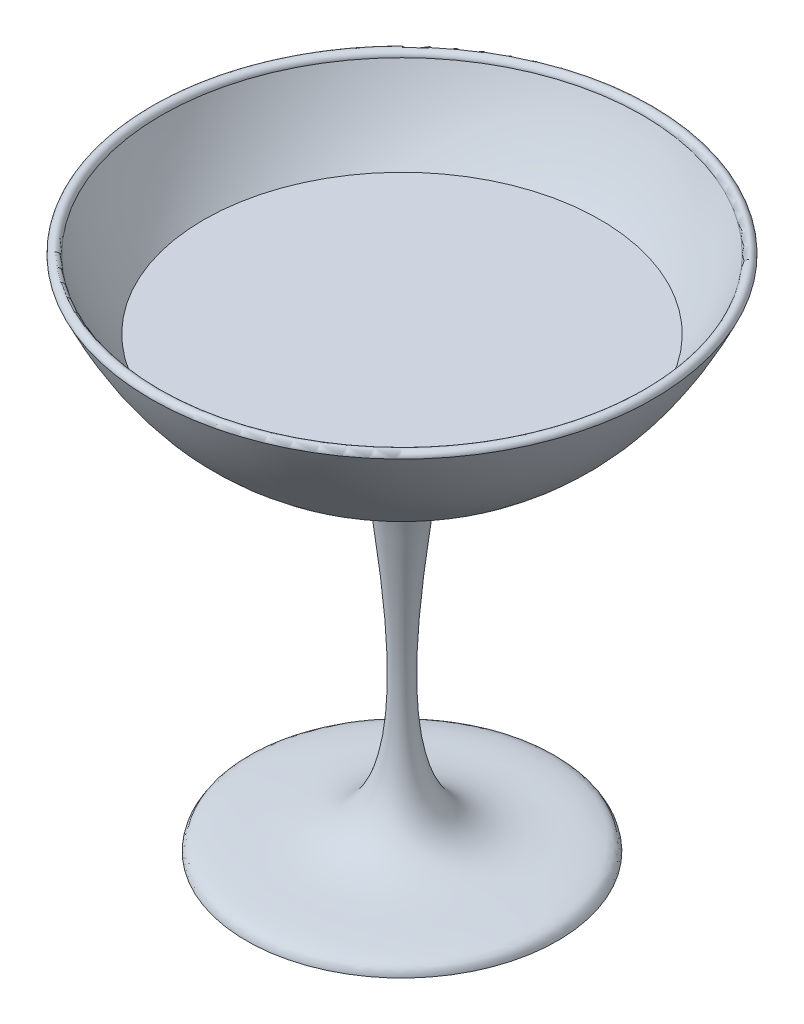
SolidWorks part; units mm, degrees
ref_plane "Front Plane" through (0, 0, 0) normal (0, 0, 1) x (1, 0, 0)
ref_plane "Top Plane" through (0, 0, 0) normal (0, 1, 0) x (1, 0, 0)
ref_plane "Right Plane" through (0, 0, 0) normal (1, 0, 0) x (0, 0, -1)
sketch "Sketch1" plane through (0, 0, 0) normal (0, 0, 1) x (1, 0, 0)
  line L0 (0, 0) -> (28.68, 0)
  line L1 (0, 0) -> (0, 65.0791)
  arc A0 (44.3797, 95.3699) -> (46.3167, 95.3699) centre (45.3482, 95.3699) cw
  spline S0 degree 3 poles (28.68, 0) (28.4996, 1.4744) (23.4478, 2.9159) (14.9099, 2.165) (0.889, 8.9598) (1.2686, 31.6363) (4.8678, 61.8552) (5.6257, 63.456) (23.9428, 69.3245) (37.5231, 76.4913) (46.3167, 95.3699) knots 0 0 0 0 0.03919 0.186236 0.242972 0.549819 0.61142 0.797382 0.838565 1 1 1 1
  spline S1 degree 3 poles (0, 65.0791) (18.3585, 68.5811) (35.1377, 73.6238) (44.3797, 95.3699) knots 0 0 0 0 1 1 1 1
revolve "Revolve1" add sketch "Sketch1" angle 360 about L1
sketch "Sketch2" plane through (0, 0, 0) normal (0, 0, 1) x (1, 0, 0)
  line L0 (0, 82.6008) -> (0, 65.4068)
  line L1 (0, 82.6008) -> (36.5554, 82.6008)
  spline S0 degree 3 poles (0, 65.4068) (13.9739, 68.0724) (27.0369, 71.5173) (36.5554, 82.6008) knots 0 0 0 0 0.761167 0.761167 0.761167 0.761167
revolve "Revolve2" add sketch "Sketch2" angle 360 about L0
